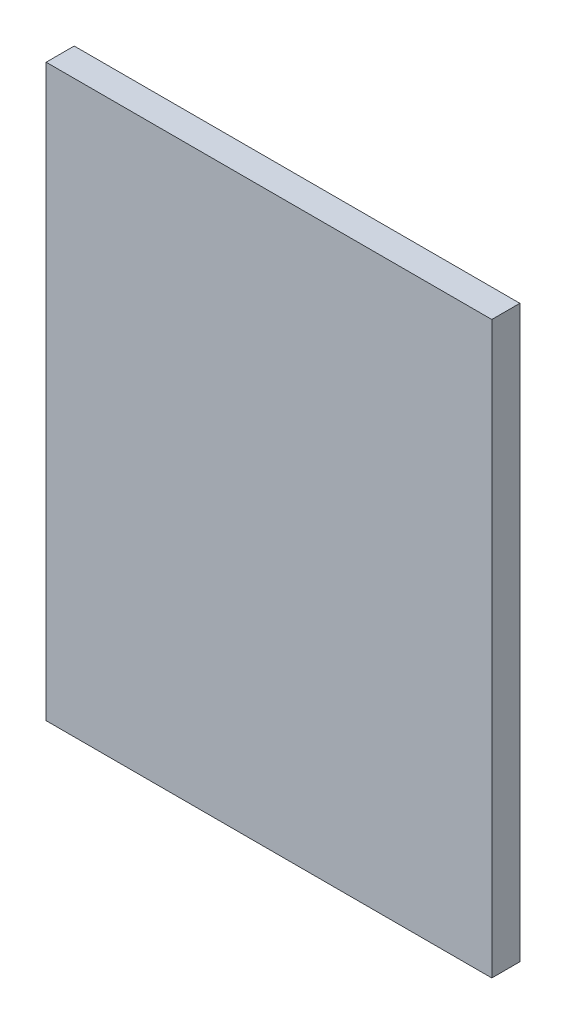
SolidWorks part; units mm, degrees
material "Buk"
ref_plane "Płaszczyzna przednia" through (0, 0, 0) normal (0, 0, 1) x (1, 0, 0)
ref_plane "Płaszczyzna górna" through (0, 0, 0) normal (0, 1, 0) x (1, 0, 0)
ref_plane "Płaszczyzna prawa" through (0, 0, 0) normal (1, 0, 0) x (0, 0, -1)
sketch "Szkic1" plane through (0, 0, 0) normal (0, 0, 1) x (1, 0, 0)
  line L8 (143, -183) -> (143, 183)
  line L9 (143, 183) -> (-143, 183)
  line L10 (-143, 183) -> (-143, -183)
  line L11 (-143, -183) -> (143, -183)
  line L12 (143, -183) -> (143, 183)
  line L13 (143, 183) -> (-143, 183)
  line L14 (-143, 183) -> (-143, -183)
  line L15 (-143, -183) -> (143, -183)
  dimension "D1" = 17
extrude "Dodanie-wyciągnięcie1" add sketch "Szkic1" along normal blind 18
